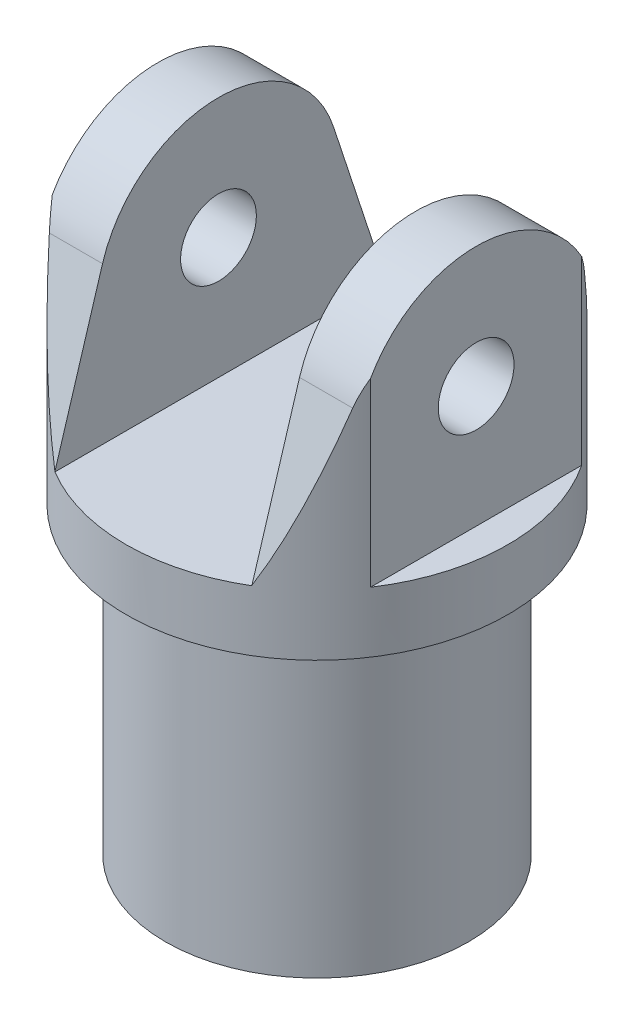
SolidWorks part; units mm, degrees
ref_plane "Front Plane" through (0, 0, 0) normal (0, 0, 1) x (1, 0, 0)
ref_plane "Top Plane" through (0, 0, 0) normal (0, 1, 0) x (1, 0, 0)
ref_plane "Right Plane" through (0, 0, 0) normal (1, 0, 0) x (0, 0, -1)
sketch "Sketch1" plane through (0, 0, 0) normal (0, 1, 0) x (1, 0, 0)
  circle A0 centre (0, 0) radius 8.001
  dimension "D1" = 16.002
extrude "Boss-Extrude1" add sketch "Sketch1" along normal blind 25.4
sketch "Sketch2" plane through (0, 0, 0) normal (0, -1, 0) x (-1, 0, 0)
  circle A0 centre (0, 0) radius 4.699
  circle A1 centre (0, 0) radius 6.35
  circle A2 centre (0, 0) radius 8.001
  circle M1 centre (0, 0) radius 8.001
  dimension "D1" = 9.398
  dimension "D2" = 12.7
extrude "Cut-Extrude1" cut sketch "Sketch2" against normal blind 12.7 contours A0 | A1 M1
sketch "Sketch3" plane through (0, 0, 0) normal (0, 0, 1) x (1, 0, 0)
  line L0 (8.001, 25.4) -> (-8.001, 25.4) construction
  line L1 (-4.1275, 25.4) -> (4.1275, 25.4)
  line L2 (-4.1275, 25.4) -> (-4.1275, 15.24)
  line L3 (-4.1275, 15.24) -> (4.1275, 15.24)
  line L4 (4.1275, 25.4) -> (4.1275, 15.24)
  line L5 (-8.001, 25.4) -> (-8.001, 12.7) construction
  line L6 (-8.001, 15.24) -> (-6.6675, 15.24)
  line L7 (-8.001, 15.24) -> (-8.001, 25.4)
  line L8 (-8.001, 25.4) -> (-6.6675, 25.4)
  line L9 (-6.6675, 15.24) -> (-6.6675, 25.4)
  line L11 (6.6675, 15.24) -> (8.001, 15.24)
  line L12 (6.6675, 15.24) -> (6.6675, 25.4)
  line L13 (6.6675, 25.4) -> (8.001, 25.4)
  line L14 (8.001, 15.24) -> (8.001, 25.4)
  dimension "D1" = 15.24
  dimension "D2" = 0
  dimension "D3" = 8.255
  dimension "D4" = 4.1275
  dimension "D5" = 2.54
  dimension "D6" = 2.54
extrude "Cut-Extrude2" cut sketch "Sketch3" against normal through all and the other way through all
sketch "Sketch4" plane through (6.6675, 0, 0) normal (1, 0, 0) x (0, 0, -1)
  line L0 (0, 25.4) -> (0, 15.24) construction
  line L1 (4.4227, 25.4) -> (-4.4227, 25.4) construction
  line L2 (4.4227, 15.24) -> (-4.4227, 15.24) construction
  line L3 (-4.8594, 21.8008) -> (-6.8587, 15.24)
  line L4 (-6.8587, 15.24) -> (-6.8587, 50.8)
  line L5 (7.0182, 15.24) -> (4.8258, 21.907)
  line L6 (-6.8587, 50.8) -> (6.956, 50.8)
  line L7 (6.956, 50.8) -> (7.0182, 15.24)
  arc A0 (4.8258, 21.907) -> (-4.8594, 21.8008) centre (0, 20.32) ccw
  circle A1 centre (0, 20.32) radius 1.5875
  line M2 (4.4227, 25.4) -> (-4.4227, 25.4)
  line M3 (-4.4227, 25.4) -> (-4.4227, 15.24)
  line M5 (4.4227, 15.24) -> (4.4227, 25.4)
  dimension "D1" = 3.175
  dimension "D2" = 25.4
extrude "Cut-Extrude3" cut sketch "Sketch4" against normal through all contours A0 L5 L7 L6 L4 L3 M3 M2 M5 | A1 L0 | L0 A1 | A0 M2 M3 | A0 M5 M2
equation "\"LinkID\"= .5in"
equation "\"LinkTHNK\"= .065in"
equation "\"TieRodWidth\"= .325in"
equation "\"D1@Sketch1\"=\"LinkID\"+2*(\"LinkTHNK\")"
equation "\"D1@Sketch2\"=\"LinkID\"-2*(\"LinkTHNK\")"
equation "\"D2@Sketch2\"=\"LinkID\""
equation "\"D3@Sketch3\"=\"TieRodWidth\""
equation "\"D4@Sketch3\"=\"D3@Sketch3\"/2"
equation "\"D6@Sketch3\"=\"D5@Sketch3\""
